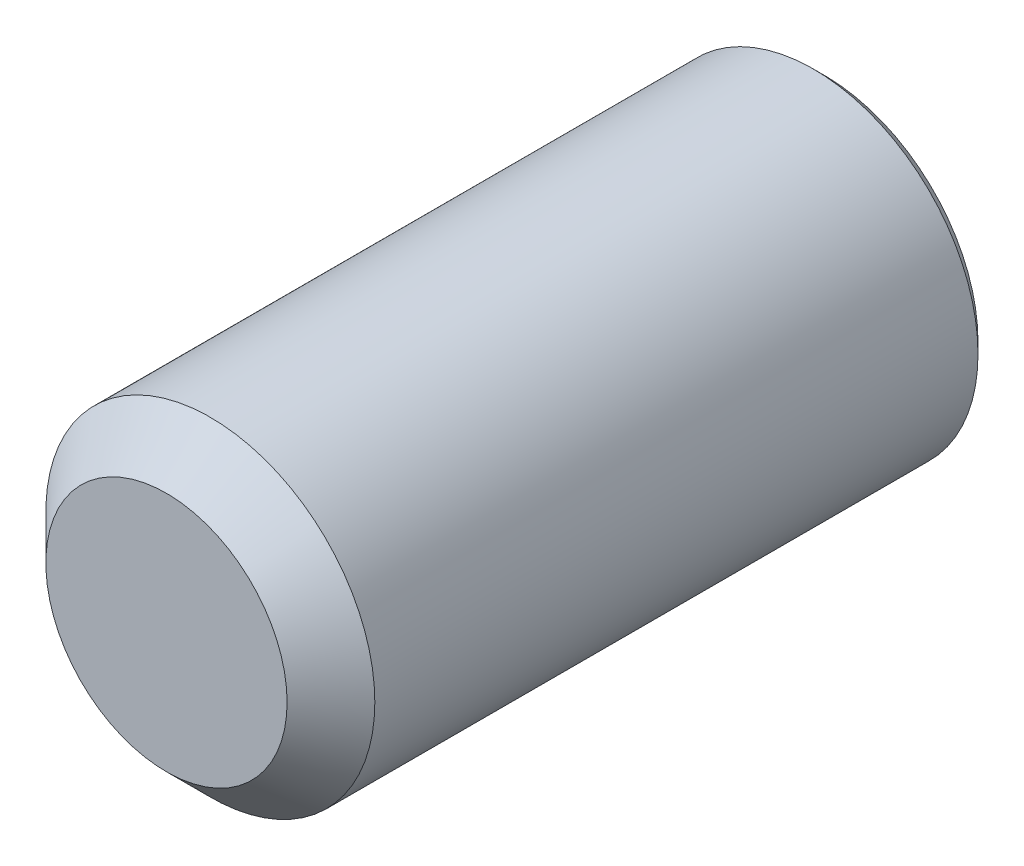
SolidWorks part; units mm, degrees
ref_plane "前视基准面" through (0, 0, 0) normal (0, 0, 1) x (1, 0, 0)
ref_plane "上视基准面" through (0, 0, 0) normal (0, 1, 0) x (1, 0, 0)
ref_plane "右视基准面" through (0, 0, 0) normal (1, 0, 0) x (0, 0, -1)
sketch "草图1" plane through (0, 0, 0) normal (0, 0, 1) x (1, 0, 0)
  circle A0 centre (0, 0) radius 1.5
  dimension "D1" = 3
extrude "凸台-拉伸1" add sketch "草图1" along normal blind 6
chamfer "倒角1" distance 0.4 angle 45 1 edges at (1.5, 0, 6)
sketch "草图2" plane through (0, 0, 0) normal (0, 0, -1) x (-1, 0, 0)
  line L1 (0.4983, 0.7083) -> (-0.3643, 0.7857)
  line L2 (-0.3643, 0.7857) -> (-0.8626, 0.0774)
  line L3 (-0.8626, 0.0774) -> (-0.4983, -0.7083)
  line L4 (-0.4983, -0.7083) -> (0.3643, -0.7857)
  line L5 (0.3643, -0.7857) -> (0.8626, -0.0774)
  line L6 (0.8626, -0.0774) -> (0.4983, 0.7083)
  circle A0 centre (0, 0) radius 0.75 construction
  dimension "D1" = 1.5
extrude "切除-拉伸1" cut sketch "草图2" against normal blind 1.2
chamfer "倒角2" distance 0.1 angle 45 13 edges at (-0.6134, -0.4315, 1.2) (0.067, -0.747, 1.2) (0.6804, -0.3155, 1.2) (0.6134, 0.4315, 1.2) (-0.067, 0.747, 1.2) (-0.6804, 0.3155, 1.2) (1.5, 0, 0) (0.6134, 0.4315, 0) (0.6804, -0.3155, 0) (0.067, -0.747, 0) (-0.6134, -0.4315, 0) (-0.6804, 0.3155, 0) (-0.067, 0.747, 0)
